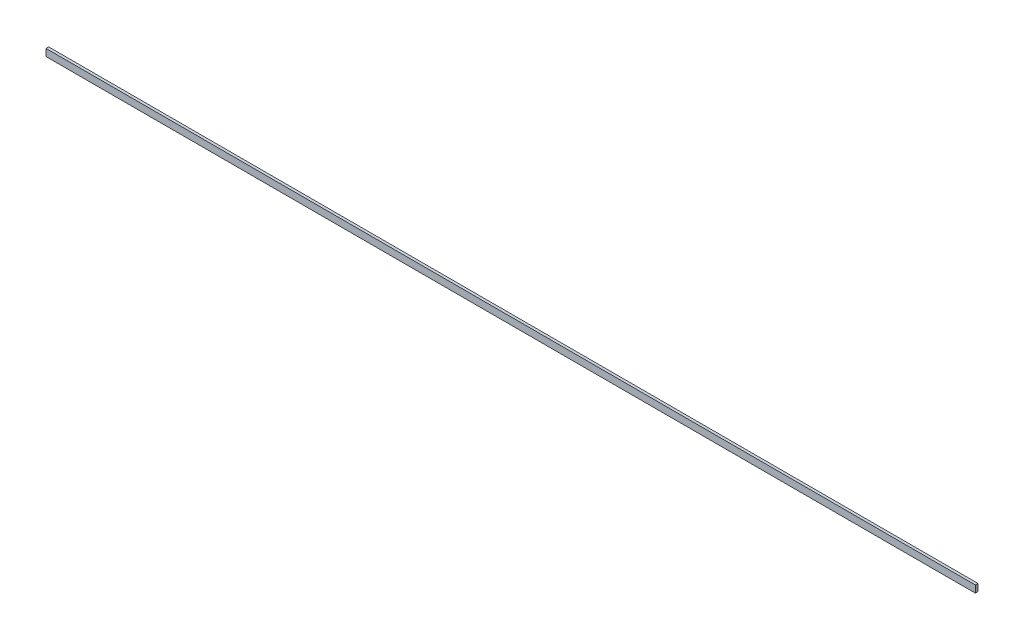
SolidWorks part; units mm, degrees
ref_plane "前视基准面" through (0, 0, 0) normal (0, 0, 1) x (1, 0, 0)
ref_plane "上视基准面" through (0, 0, 0) normal (0, 1, 0) x (1, 0, 0)
ref_plane "右视基准面" through (0, 0, 0) normal (1, 0, 0) x (0, 0, -1)
sketch "草图1" plane through (0, 0, 0) normal (0, 0, 1) x (1, 0, 0)
  line L1 (0, 0) -> (525, 0)
  line L2 (0, 0) -> (0, -4)
  line L3 (0, -4) -> (525, -4)
  line L4 (525, 0) -> (525, -4)
  dimension "D1" = 4
  dimension "D2" = 525
extrude "凸台-拉伸1" add sketch "草图1" along normal blind 1.5
